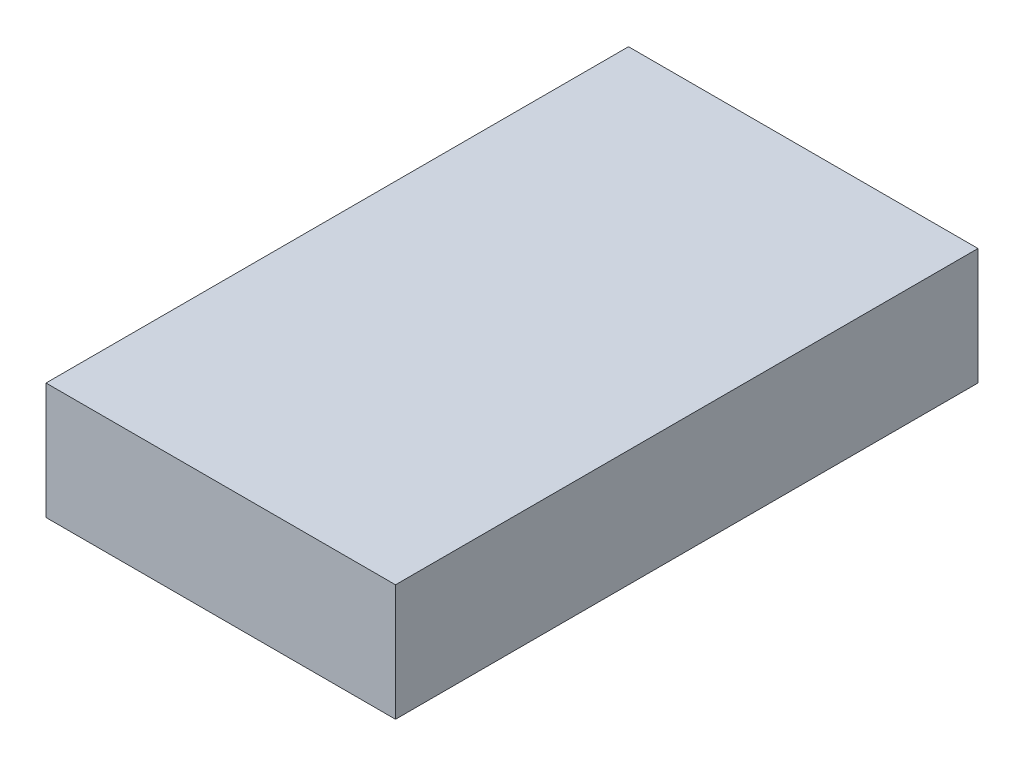
SolidWorks part; units mm, degrees
material "混合材料"
ref_plane "前视基准面" through (0, 0, 0) normal (0, 0, 1) x (1, 0, 0)
ref_plane "上视基准面" through (0, 0, 0) normal (0, 1, 0) x (1, 0, 0)
ref_plane "右视基准面" through (0, 0, 0) normal (1, 0, 0) x (0, 0, -1)
sketch "草图1" plane through (0, 0, 0) normal (0, 1, 0) x (1, 0, 0)
  line L5 (-75, -125) -> (75, -125)
  line L6 (-75, -125) -> (-75, 125)
  line L7 (-75, 125) -> (75, 125)
  line L8 (75, -125) -> (75, 125)
  line L9 (-75, -125) -> (75, 125) construction
  line L10 (-75, 125) -> (75, -125) construction
  point P0 (0, 0)
  dimension "D1" = 250
  dimension "D2" = 150
extrude "凸台-拉伸1" add sketch "草图1" along normal blind 50
